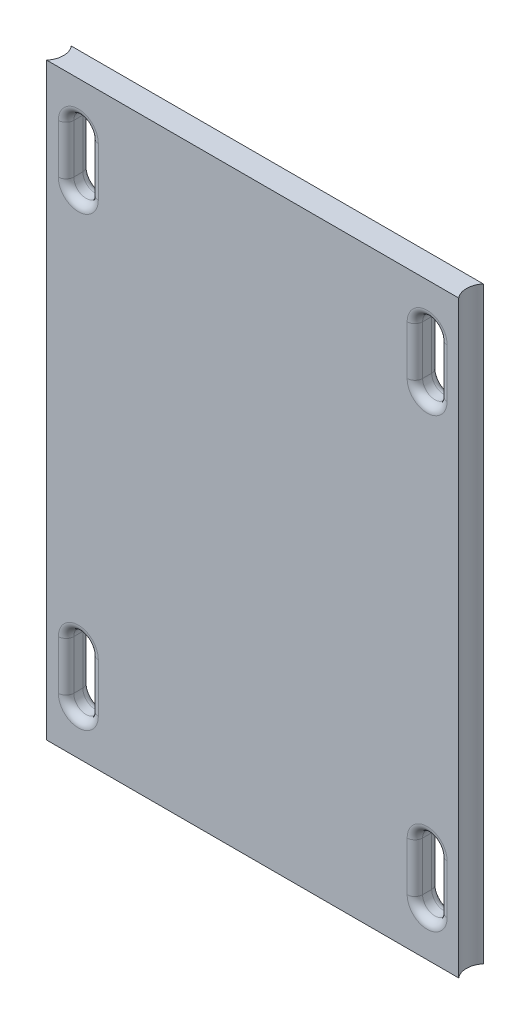
SolidWorks part; units mm, degrees
ref_plane "Front Plane" through (0, 0, 0) normal (0, 0, 1) x (1, 0, 0)
ref_plane "Top Plane" through (0, 0, 0) normal (0, 1, 0) x (1, 0, 0)
ref_plane "Right Plane" through (0, 0, 0) normal (1, 0, 0) x (0, 0, -1)
sketch "Sketch1" plane through (0, 0, 0) normal (0, 1, 0) x (1, 0, 0)
  line L1 (-28.575, -1.5875) -> (28.575, -1.5875)
  line L2 (-28.575, -1.5875) -> (-28.575, 1.5875)
  line L3 (-28.575, 1.5875) -> (28.575, 1.5875)
  line L4 (28.575, -1.5875) -> (28.575, 1.5875)
  line L5 (-28.575, -1.5875) -> (28.575, 1.5875) construction
  line L6 (-28.575, 1.5875) -> (28.575, -1.5875) construction
  circle A0 centre (-28.575, 0) radius 2.4892
  circle A1 centre (28.575, 0) radius 2.4892
  point P0 (0, 0)
  dimension "D2" = 54.6608
  dimension "D3" = 4.9784
  dimension "D1" = 3.175
  dimension "D4" = 57.15
extrude "Boss-Extrude1" add sketch "Sketch1" along normal blind 76.2 contours A1 L3 A0 L1
sketch "Sketch2" plane through (0, 0, 1.5875) normal (0, 0, 1) x (1, 0, 0)
  line L0 (0, 76.2) -> (0, 0) construction
  line L1 (-26.6577, 76.2) -> (26.6577, 76.2) construction
  line L2 (-26.6577, 38.1) -> (26.6577, 38.1) construction
  line L3 (-26.6577, 76.2) -> (-26.6577, 0) construction
  line L4 (26.6577, 76.2) -> (26.6577, 0) construction
  line L5 (-22.5702, 70.2) -> (-22.5702, 63.85) construction
  line L6 (-20.9827, 70.2) -> (-20.9827, 63.85)
  line L7 (-24.1577, 70.2) -> (-24.1577, 63.85)
  line L8 (22.5702, 70.2) -> (22.5702, 63.85) construction
  line L9 (20.9827, 70.2) -> (20.9827, 63.85)
  line L10 (24.1577, 70.2) -> (24.1577, 63.85)
  line L11 (22.5702, 6) -> (22.5702, 12.35) construction
  line L12 (20.9827, 6) -> (20.9827, 12.35)
  line L13 (24.1577, 6) -> (24.1577, 12.35)
  line L14 (-22.5702, 6) -> (-22.5702, 12.35) construction
  line L15 (-20.9827, 6) -> (-20.9827, 12.35)
  line L16 (-24.1577, 6) -> (-24.1577, 12.35)
  arc A0 (-20.9827, 70.2) -> (-24.1577, 70.2) centre (-22.5702, 70.2) ccw
  arc A1 (-24.1577, 63.85) -> (-20.9827, 63.85) centre (-22.5702, 63.85) ccw
  arc A2 (20.9827, 70.2) -> (24.1577, 70.2) centre (22.5702, 70.2) cw
  arc A3 (24.1577, 63.85) -> (20.9827, 63.85) centre (22.5702, 63.85) cw
  arc A4 (20.9827, 6) -> (24.1577, 6) centre (22.5702, 6) ccw
  arc A5 (24.1577, 12.35) -> (20.9827, 12.35) centre (22.5702, 12.35) ccw
  arc A6 (-20.9827, 6) -> (-24.1577, 6) centre (-22.5702, 6) cw
  arc A7 (-24.1577, 12.35) -> (-20.9827, 12.35) centre (-22.5702, 12.35) cw
  point P13 (-22.5702, 67.025)
  point P21 (22.5702, 67.025)
  point P28 (22.5702, 9.175)
  point P35 (-22.5702, 9.175)
  dimension "D2" = 1.5875
  dimension "D1" = 6.35
  dimension "D3" = 2.5
  dimension "D4" = 6
extrude "Cut-Extrude1" cut sketch "Sketch2" against normal through all both and the other way through all
fillet "Fillet1" radius 1 32 edges at (24.1577, 67.025, 1.5875) (22.5702, 71.7875, 1.5875) (20.9827, 67.025, 1.5875) (20.9827, 67.025, -1.5875) (22.5702, 71.7875, -1.5875) (24.1577, 67.025, -1.5875) (24.1577, 9.175, 1.5875) (22.5702, 13.9375, 1.5875) (20.9827, 9.175, 1.5875) (20.9827, 9.175, -1.5875) (22.5702, 13.9375, -1.5875) (24.1577, 9.175, -1.5875) (-20.9827, 9.175, 1.5875) (-22.5702, 13.9375, 1.5875) (-24.1577, 9.175, 1.5875) (-24.1577, 9.175, -1.5875) (-22.5702, 13.9375, -1.5875) (-20.9827, 9.175, -1.5875) (-20.9827, 67.025, 1.5875) (-22.5702, 71.7875, 1.5875) (-24.1577, 67.025, 1.5875) (-24.1577, 67.025, -1.5875) (-22.5702, 71.7875, -1.5875) (-20.9827, 67.025, -1.5875) (22.5702, 62.2625, 1.5875) (22.5702, 62.2625, -1.5875) (22.5702, 4.4125, 1.5875) (22.5702, 4.4125, -1.5875) (-22.5702, 4.4125, 1.5875) (-22.5702, 4.4125, -1.5875) (-22.5702, 62.2625, 1.5875) (-22.5702, 62.2625, -1.5875)
